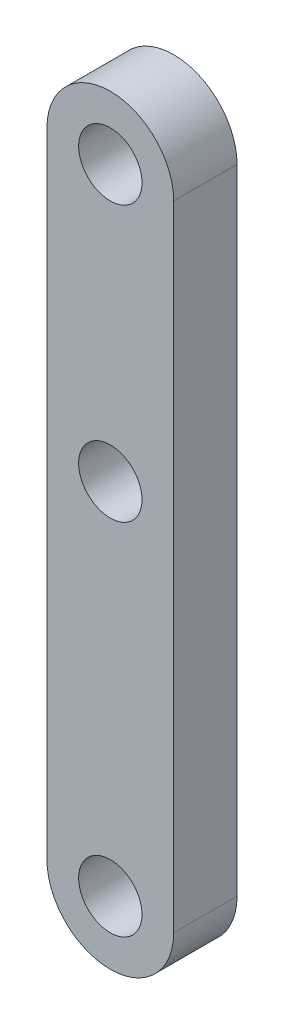
SolidWorks part; units mm, degrees
ref_plane "正面" through (0, 0, 0) normal (0, 0, 1) x (1, 0, 0)
ref_plane "平面" through (0, 0, 0) normal (0, 1, 0) x (1, 0, 0)
ref_plane "右側面" through (0, 0, 0) normal (1, 0, 0) x (0, 0, -1)
sketch "ｽｹｯﾁ1" plane through (0, 0, 0) normal (0, 0, 1) x (1, 0, 0)
  line L0 (0, 0) -> (0, -30) construction
  line L1 (-3, 0) -> (-3, -30)
  line L2 (3, 0) -> (3, -8)
  line L3 (0, -15) -> (-3, -15) construction
  line L4 (3, -8) -> (18, -8) construction
  line L5 (3, -12) -> (9, -12) construction
  line L6 (3, -12) -> (3, -30)
  line L7 (3, -8) -> (3, -12) construction
  line L8 (18, -8) -> (18, -18) construction
  line L9 (18, -18) -> (15, -18) construction
  line L10 (15, -18) -> (15, -12) construction
  line L11 (15, -12) -> (12, -12) construction
  line L12 (12, -12) -> (12, -18) construction
  line L13 (12, -18) -> (9, -18) construction
  line L14 (9, -18) -> (9, -12) construction
  line L15 (3, -8) -> (3, -12)
  circle A0 centre (0, 0) radius 1.5
  arc A1 (3, 0) -> (-3, 0) centre (0, 0) ccw
  circle A2 centre (0, -30) radius 1.5
  arc A3 (3, -30) -> (-3, -30) centre (0, -30) cw
  arc A4 (0, -3) -> (3, 0) centre (0, 0) ccw construction
  arc A5 (-3, 0) -> (0, -3) centre (0, 0) ccw construction
  arc A6 (-3, -30) -> (0, -27) centre (0, -30) cw construction
  arc A7 (0, -27) -> (3, -30) centre (0, -30) cw construction
  circle A9 centre (0, -13) radius 1.5
  dimension "D1" = 3
  dimension "D2" = 6
  dimension "D5" = 4
  dimension "D11" = 3
  dimension "D3" = 6
  dimension "D4" = 30
  dimension "D6" = 15
  dimension "D7" = 3
  dimension "D8" = 3
  dimension "D9" = 12
  dimension "D10" = 6
  dimension "D12" = 13
extrude "ﾎﾞｽ - 押し出し1" add sketch "ｽｹｯﾁ1" along normal blind 3
fillet "ﾌｨﾚｯﾄ1" [suppressed] radius 3
fillet "ﾌｨﾚｯﾄ2" [suppressed] radius 1
